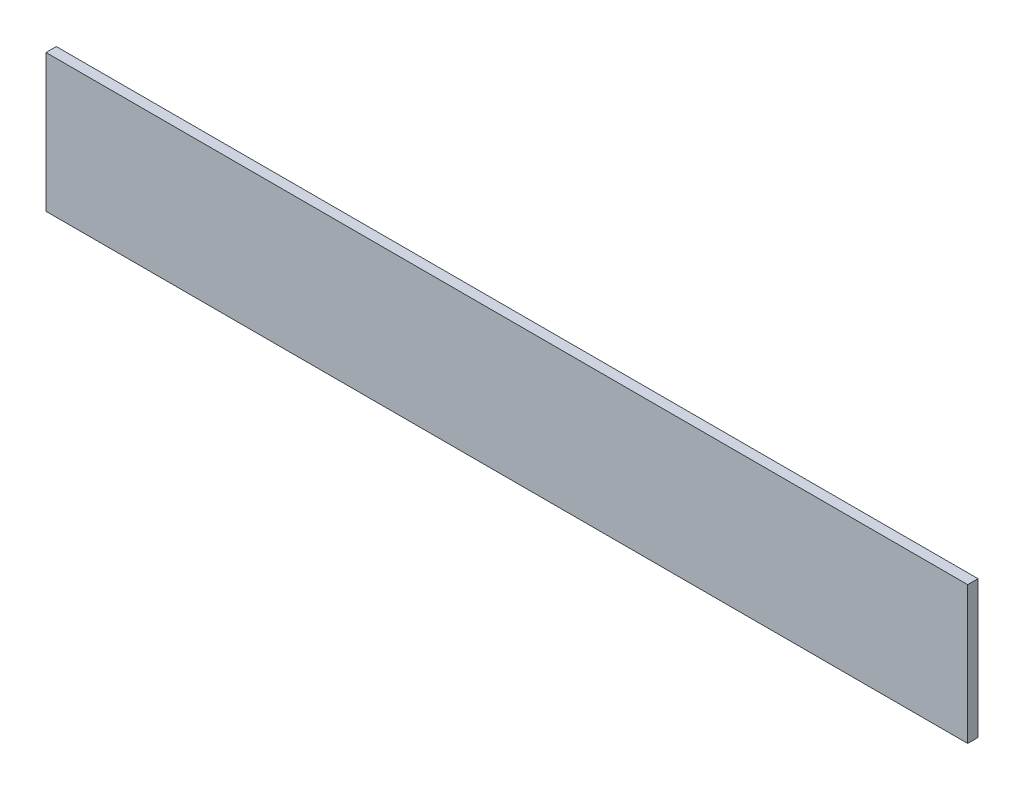
SolidWorks part; units mm, degrees
ref_plane "Front Plane" through (0, 0, 0) normal (0, 0, 1) x (1, 0, 0)
ref_plane "Top Plane" through (0, 0, 0) normal (0, 1, 0) x (1, 0, 0)
ref_plane "Right Plane" through (0, 0, 0) normal (1, 0, 0) x (0, 0, -1)
sketch "Sketch1" plane through (0, 0, 0) normal (0, 0, 1) x (1, 0, 0)
  line L1 (0, 0) -> (425.45, 0)
  line L2 (0, 0) -> (0, 63.5)
  line L3 (0, 63.5) -> (425.45, 63.5)
  line L4 (425.45, 0) -> (425.45, 63.5)
  dimension "D1" = 425.45
extrude "Boss-Extrude1" add sketch "Sketch1" along normal blind 4.7625
